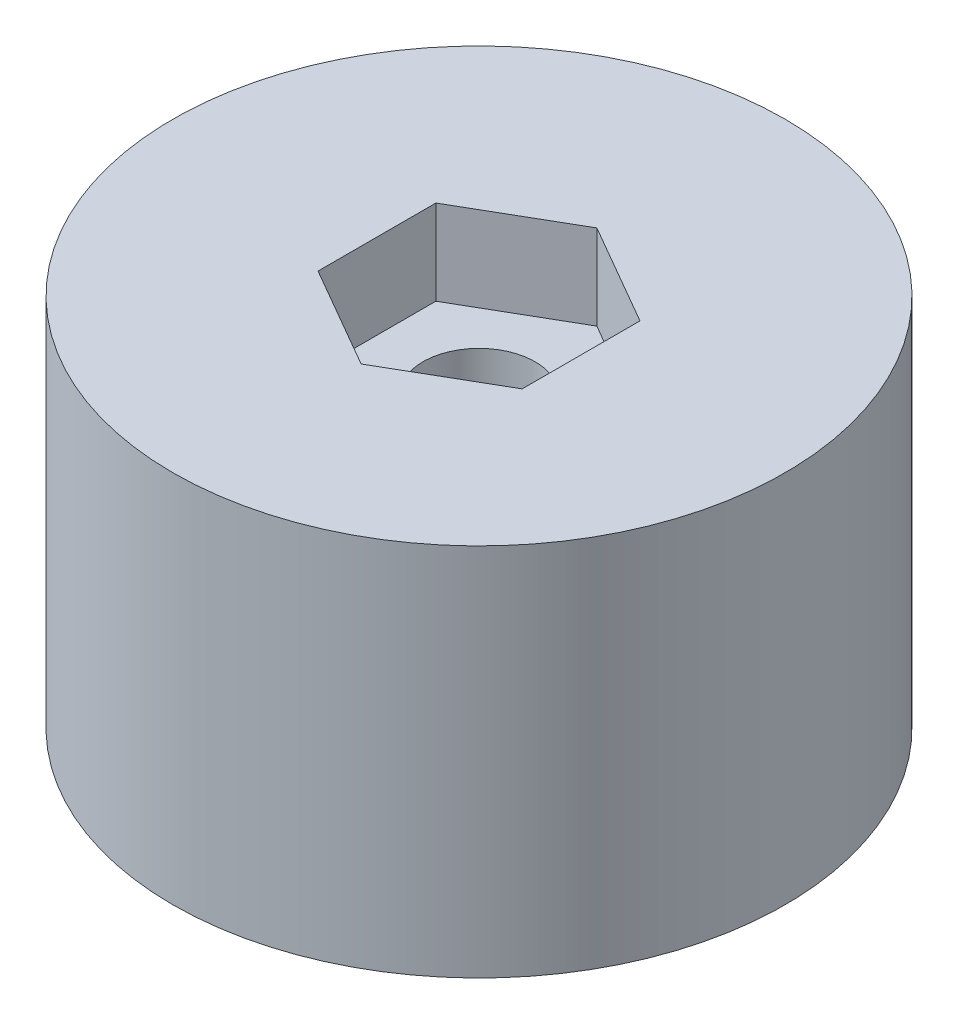
SolidWorks part; units mm, degrees
ref_plane "Front Plane" through (0, 0, 0) normal (0, 0, 1) x (1, 0, 0)
ref_plane "Top Plane" through (0, 0, 0) normal (0, 1, 0) x (1, 0, 0)
ref_plane "Right Plane" through (0, 0, 0) normal (1, 0, 0) x (0, 0, -1)
sketch "Sketch1" plane through (0, 0, 0) normal (0, 1, 0) x (1, 0, 0)
  circle A0 centre (0, 0) radius 9
  dimension "D1" = 18
extrude "Boss-Extrude1" add sketch "Sketch1" along normal blind 11
sketch "Sketch2" plane through (0, 11, 0) normal (0, 1, 0) x (1, 0, 0)
  circle A0 centre (0, 0) radius 1.65
  dimension "D1" = 3.3
extrude "Cut-Extrude1" cut sketch "Sketch2" against normal up to next
sketch "Sketch3" plane through (0, 11, 0) normal (0, 1, 0) x (1, 0, 0)
  line L1 (3, -1.7321) -> (3, 1.7321)
  line L2 (3, 1.7321) -> (0, 3.4641)
  line L3 (0, 3.4641) -> (-3, 1.7321)
  line L4 (-3, 1.7321) -> (-3, -1.7321)
  line L5 (-3, -1.7321) -> (0, -3.4641)
  line L6 (0, -3.4641) -> (3, -1.7321)
  circle A0 centre (0, 0) radius 3 construction
  point P1 (-4.6051, -2.6655)
  point P10 (-4.825, -2.7857)
  dimension "D1" = 6
extrude "Cut-Extrude2" cut sketch "Sketch3" against normal blind 2.5
